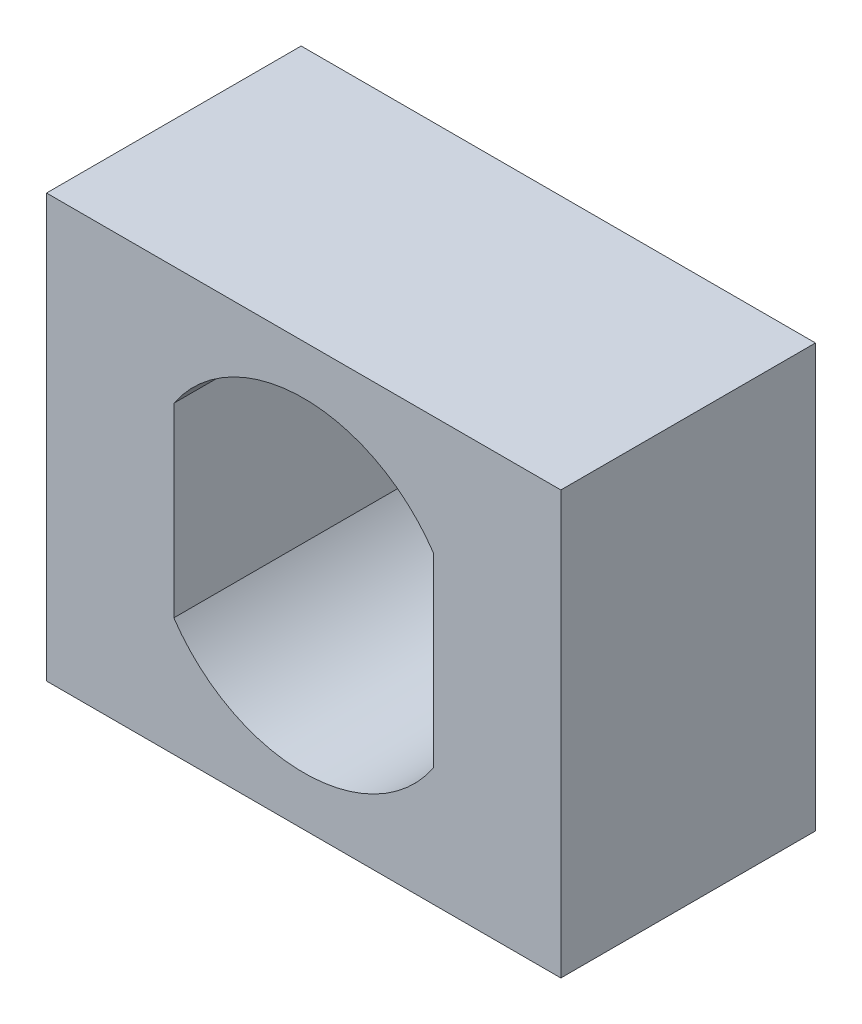
SolidWorks part; units mm, degrees
ref_plane "Alzado" through (0, 0, 0) normal (0, 0, 1) x (1, 0, 0)
ref_plane "Planta" through (0, 0, 0) normal (0, 1, 0) x (1, 0, 0)
ref_plane "Vista lateral" through (0, 0, 0) normal (1, 0, 0) x (0, 0, -1)
sketch "Croquis1" plane through (0, 0, 0) normal (0, 0, 1) x (1, 0, 0)
  line L1 (-10.1, 8.3) -> (10.1, 8.3)
  line L2 (-10.1, 8.3) -> (-10.1, -8.3)
  line L3 (-10.1, -8.3) -> (10.1, -8.3)
  line L4 (10.1, 8.3) -> (10.1, -8.3)
  line L5 (-10.1, 8.3) -> (10.1, -8.3) construction
  line L6 (-10.1, -8.3) -> (10.1, 8.3) construction
  point P0 (0, 0)
  dimension "D1" = 20.2
  dimension "D2" = 16.6
extrude "Saliente-Extruir1" add sketch "Croquis1" along normal blind 10
sketch "Croquis2" plane through (0, 0, 10) normal (0, 0, 1) x (1, 0, 0)
  line L0 (-5.1, -3.65) -> (-5.1, 3.65)
  line L1 (-10.1, 0) -> (10.1, 0) construction
  line L2 (-10.1, 8.3) -> (-10.1, -8.3) construction
  line L3 (10.1, -8.3) -> (10.1, 8.3) construction
  line L4 (5.1, 3.65) -> (5.1, -3.65)
  line L5 (-5.1, 3.65) -> (5.1, 3.65) construction
  line L6 (0, 0) -> (0, 5.8898) construction
  arc A0 (-5.1, 3.65) -> (5.1, 3.65) centre (0, 0.2288) cw
  arc A1 (-5.1, -3.65) -> (5.1, -3.65) centre (0, -0.2288) ccw
  point P8 (-5.1, 0)
  point P14 (0, 3.65)
  point P16 (0, 6.37)
  dimension "D1" = 10.2
  dimension "D2" = 2.72
  dimension "D3" = 7.3
extrude "Cortar-Extruir1" cut sketch "Croquis2" against normal blind 10
